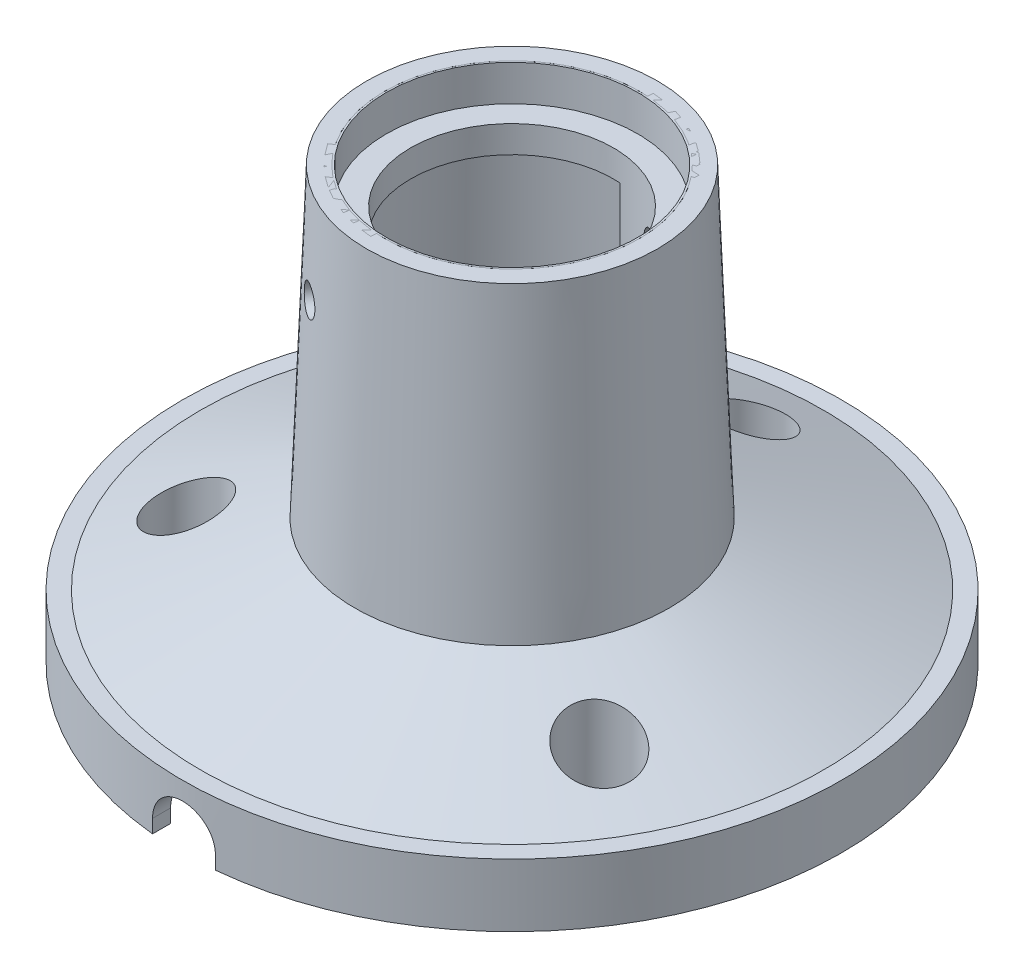
SolidWorks part; units mm, degrees
ref_plane "정면" through (0, 0, 0) normal (0, 0, 1) x (1, 0, 0)
ref_plane "윗면" through (0, 0, 0) normal (0, 1, 0) x (1, 0, 0)
ref_plane "우측면" through (0, 0, 0) normal (1, 0, 0) x (0, 0, -1)
sketch "스케치2" plane through (0, 0, 0) normal (0, 0, 1) x (1, 0, 0)
  line L0 (0, 0) -> (36.7, 0)
  line L1 (36.7, 0) -> (36.7, 7)
  line L2 (36.7, 7) -> (34.7, 7)
  line L3 (34.7, 7) -> (17.5, 14)
  line L4 (17.5, 14) -> (16.2, 48)
  line L5 (16.2, 48) -> (0, 48)
  line L6 (0, 48) -> (0, 0)
  point P3 (14.3509, 25.3039)
  dimension "D1" = 36.7
  dimension "D2" = 16.2
  dimension "D3" = 17.5
  dimension "D4" = 48
  dimension "D5" = 14
  dimension "D6" = 7
  dimension "D7" = 2
revolve "회전1" add sketch "스케치2" angle 360 about L6
sketch "스케치4" plane through (0, 48, 0) normal (0, 1, 0) x (1, 0, 0)
  line L0 (0, 0) -> (0, 26.5581) construction
  line L1 (0, 26.5581) -> (-23, -13.2791) construction
  line L2 (-23, -13.2791) -> (0, 0) construction
  line L3 (-23, -13.2791) -> (23, -13.2791) construction
  line L4 (23, -13.2791) -> (0, 26.5581) construction
  circle A0 centre (0, 26.5581) radius 3.9
  circle A1 centre (-23, -13.2791) radius 3.9
  circle A2 centre (23, -13.2791) radius 3.9
  point P6 (0, 0)
  dimension "D1" = 7.8
  dimension "D2" = 46
extrude "컷-돌출1" cut sketch "스케치4" against normal offset from surface (46 mm away) 2 up to face at (-36.7, 0, 0)
shell "쉘3" thickness 2
sketch "스케치6" plane through (0, 48, 0) normal (0, 1, 0) x (1, 0, 0)
  circle A0 centre (0, 26.5581) radius 2.25
  circle A1 centre (-23, -13.2791) radius 2.25
  circle A2 centre (23, -13.2791) radius 2.25
  point P9 (23, -13.2791)
  dimension "D1" = 4.5
extrude "컷-돌출2" cut sketch "스케치6" against normal through all
sketch "스케치7" plane through (0, 48, 0) normal (0, 1, 0) x (1, 0, 0)
  circle A0 centre (0, 0) radius 14.1985
  circle A1 centre (0, 0) radius 11.3
  circle A2 centre (0, 0) radius 14.1985 construction
  dimension "D1" = 22.6
extrude "보스-돌출1" add sketch "스케치7" against normal blind 7
sketch "스케치8" plane through (0, 48, 0) normal (0, 1, 0) x (1, 0, 0)
  line L0 (-11.4646, -19.8572) -> (11.4646, 19.8572) construction
  line L1 (9.3969, 6.276) -> (12.3075, 8.2198)
  line L3 (0.9649, 14.7685) -> (0.7367, 11.276)
  line L4 (-0.7367, -11.276) -> (-0.9649, -14.7685)
  line L6 (-12.3075, -8.2198) -> (-9.3969, -6.276)
  line L7 (-9.3969, -6.276) -> (9.3969, 6.276) construction
  line L8 (0, 0) -> (0, 20.2806) construction
  arc A0 (9.3969, 6.276) -> (0.7367, 11.276) centre (0, 0) ccw
  arc A1 (12.3075, 8.2198) -> (0.9649, 14.7685) centre (0, 0) ccw
  arc A2 (-9.3969, -6.276) -> (-0.7367, -11.276) centre (0, 0) ccw
  arc A3 (-12.3075, -8.2198) -> (-0.9649, -14.7685) centre (0, 0) ccw
  circle A4 centre (0, 0) radius 11.3 construction
  dimension "D3" = 14.8
  dimension "D1" = 10
  dimension "D2" = 30
extrude "보스-돌출2" add sketch "스케치8" against normal blind 16
sketch "스케치9" plane through (0, 48, 0) normal (0, 1, 0) x (1, 0, 0)
  circle A0 centre (0, 0) radius 14
  circle A1 centre (0, 0) radius 11.3
  dimension "D1" = 22.6
  dimension "D2" = 28
extrude "컷-돌출3" cut sketch "스케치9" against normal blind 4
sketch "스케치10" plane through (0, 0, 0) normal (0, 1, 0) x (1, 0, 0)
  line L0 (0, 26.5581) -> (0, 0) construction
  line L1 (0, 0) -> (-23, -13.2791) construction
  line L3 (23, -13.2791) -> (0, 0) construction
  line L7 (-1, 35.2984) -> (-1, 30.3277)
  line L9 (1, 30.3277) -> (1, 35.2984)
  line L10 (1, 35.2984) -> (-1, 35.2984)
  line L11 (31.0693, -16.7832) -> (26.7646, -14.2978)
  line L12 (25.7646, -16.0299) -> (30.0693, -18.5152)
  line L13 (30.0693, -18.5152) -> (31.0693, -16.7832)
  line L14 (-30.0693, -18.5152) -> (-25.7646, -16.0299)
  line L15 (-26.7646, -14.2978) -> (-31.0693, -16.7832)
  line L16 (-31.0693, -16.7832) -> (-30.0693, -18.5152)
  arc A0 (1, 30.3277) -> (-1, 30.3277) centre (0, 26.5581) ccw
  circle A1 centre (0, 26.5581) radius 3.9 construction
  arc A2 (25.7646, -16.0299) -> (26.7646, -14.2978) centre (23, -13.2791) ccw
  arc A3 (-26.7646, -14.2978) -> (-25.7646, -16.0299) centre (-23, -13.2791) ccw
  dimension "D1" = 2
  dimension "D2" = 3
extrude "보스-돌출3" add sketch "스케치10" along normal up to surface (6.6134 mm away)
ref_plane "평면1" through (5.0668, 0, -8.776) normal (0.5, 0, -0.866) x (-0.866, 0, -0.5)
sketch "스케치11" plane through (5.0668, 0, -8.776) normal (0.5, 0, -0.866) x (-0.866, 0, -0.5)
  line L0 (0, 48) -> (10.1403, 48) construction
  circle A0 centre (0, 38) radius 1.6
  point P5 (0, 0)
  dimension "D1" = 3.2
  dimension "D2" = 10
extrude "컷-돌출4" cut sketch "스케치11" against normal through all both and the other way through all
sketch "스케치12" plane through (0, 0, 0) normal (0, 0, 1) x (1, 0, 0)
  line L0 (0, 0) -> (0, 1.5) construction
  line L1 (-3.5, 0) -> (-3.5, 1.5)
  line L2 (3.5, 0) -> (3.5, 1.5)
  line L3 (-36.7, 0) -> (36.7, 0) construction
  arc A0 (-3.5, 0) -> (3.5, 0) centre (0, 0) ccw
  arc A1 (3.5, 1.5) -> (-3.5, 1.5) centre (0, 1.5) ccw
  point P3 (0, 0.75)
  point P8 (0, 2.2661)
  dimension "D1" = 3.5
  dimension "D2" = 1.5
extrude "컷-돌출5" cut sketch "스케치12" along normal through all
